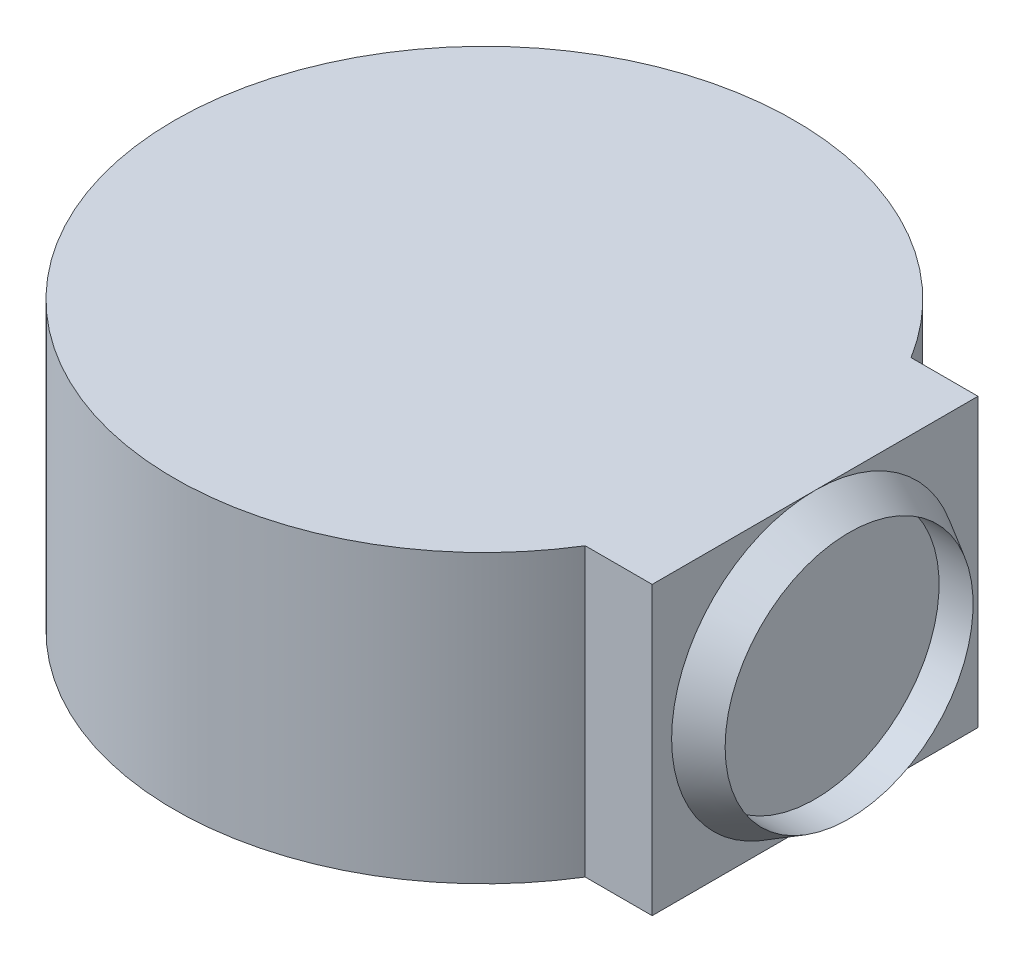
SolidWorks part; units mm, degrees
ref_plane "Front Plane" through (0, 0, 0) normal (0, 0, 1) x (1, 0, 0)
ref_plane "Top Plane" through (0, 0, 0) normal (0, 1, 0) x (1, 0, 0)
ref_plane "Right Plane" through (0, 0, 0) normal (1, 0, 0) x (0, 0, -1)
sketch "Sketch1" plane through (0, 0, 0) normal (0, 1, 0) x (1, 0, 0)
  circle A0 centre (0, 0) radius 159.375
extrude "Boss-Extrude1" add sketch "Sketch1" along normal blind 147.5
sketch "Sketch2" plane through (0, 0, 0) normal (1, 0, 0) x (0, 0, -1)
  line L1 (159.375, 147.5) -> (-159.375, 147.5) construction
  line L3 (-83.75, 147.5) -> (-83.75, 0)
  line L4 (-159.375, 0) -> (159.375, 0) construction
  line L5 (-83.75, 0) -> (83.75, 0)
  line L6 (83.75, 0) -> (83.75, 147.5)
  line L7 (83.75, 147.5) -> (-83.75, 147.5)
extrude "Boss-Extrude2" add sketch "Sketch2" along normal blind 170
sketch "Sketch3" plane through (170, 0, 0) normal (1, 0, 0) x (0, 0, -1)
  line L0 (0, 0) -> (0, 20) construction
  line L1 (-83.75, 0) -> (83.75, 0) construction
sketch "Sketch4" plane through (0, 0, 0) normal (0, 0, 1) x (1, 0, 0)
  line L0 (170, 0) -> (170, 10)
  line L1 (170, 0) -> (170, 20) construction
  line L2 (170, 0) -> (170, 147.5) construction
  line L3 (170, 10) -> (187.5, 10)
  line L4 (187.5, 10) -> (170, 0)
  line L5 (170, 0) -> (170, 73.75) construction
  line L6 (170, 73.75) -> (215.633, 73.75) construction
  point P11 (182.9962, 19.0796)
revolve "Revolve1" add sketch "Sketch4" angle 360 about L6
sketch "Sketch5" plane through (0, 0, 0) normal (0, -1, 0) x (-1, 0, 0)
  circle A0 centre (0, 0) radius 132.8125
extrude "Boss-Extrude3" add sketch "Sketch5" along normal blind 10
